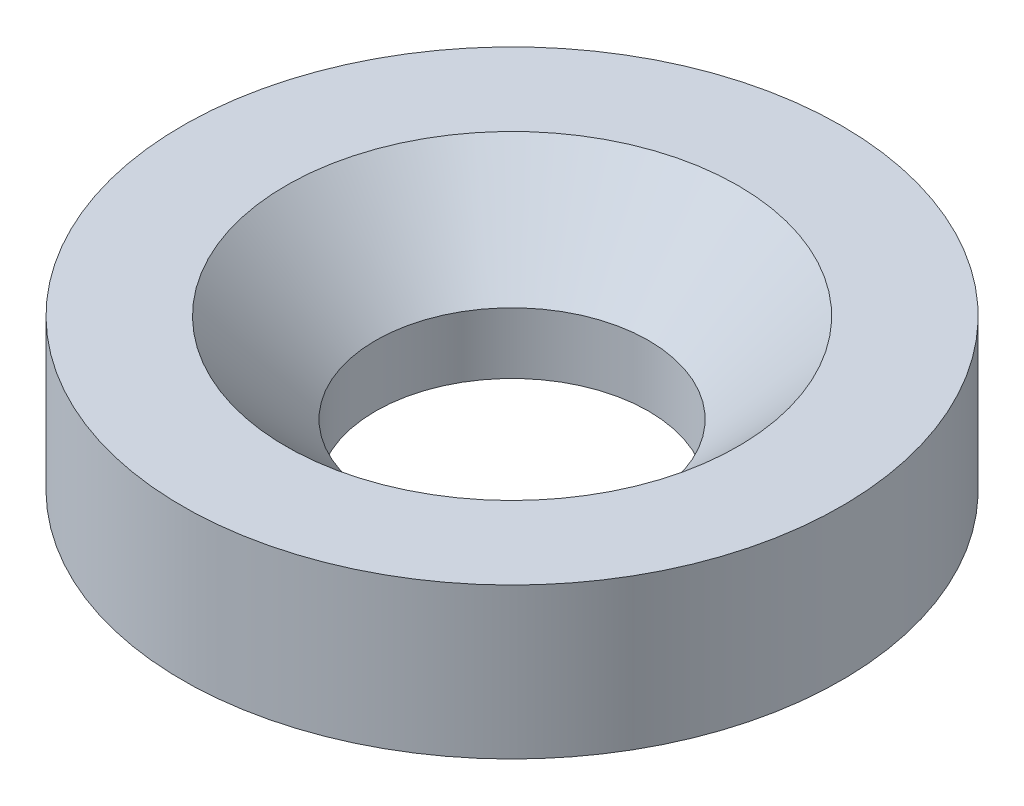
SolidWorks part; units mm, degrees
material "AISI 1020"
ref_plane "Front Plane" through (0, 0, 0) normal (0, 0, 1) x (1, 0, 0)
ref_plane "Top Plane" through (0, 0, 0) normal (0, 1, 0) x (1, 0, 0)
ref_plane "Right Plane" through (0, 0, 0) normal (1, 0, 0) x (0, 0, -1)
sketch "Sketch1" plane through (0, 0, 0) normal (0, 0, 1) x (1, 0, 0)
  line L0 (7.25, 0) -> (17.5, 0)
  line L1 (17.5, 0) -> (17.5, 8)
  line L2 (17.5, 8) -> (12, 8)
  line L3 (12, 8) -> (7.25, 3.25)
  line L4 (7.25, 3.25) -> (7.25, 0)
  line L5 (0, 0) -> (0, 8) construction
  point P8 (0, 0)
  dimension "D1" = 7.25
  dimension "D2" = 17.5
  dimension "D3" = 8
  dimension "D4" = 12
  dimension "D5" = 45
revolve "Revolve1" add sketch "Sketch1" angle 360 about L5
